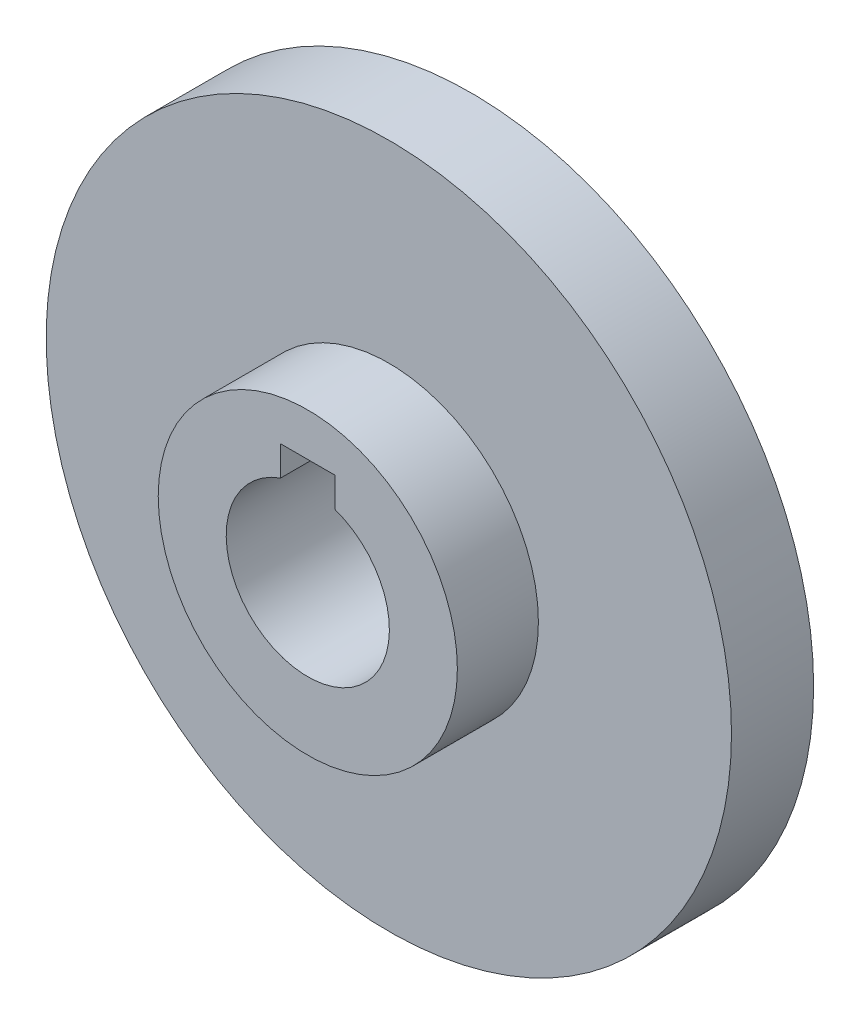
SolidWorks part; units mm, degrees
ref_plane "Front Plane" through (0, 0, 0) normal (0, 0, 1) x (1, 0, 0)
ref_plane "Top Plane" through (0, 0, 0) normal (0, 1, 0) x (1, 0, 0)
ref_plane "Right Plane" through (0, 0, 0) normal (1, 0, 0) x (0, 0, -1)
sketch "Sketch2" plane through (0, 0, 0) normal (0, 0, 1) x (1, 0, 0)
  circle A0 centre (0, 0) radius 31.5
  circle A1 centre (0, 0) radius 7.5
  dimension "D1" = 63
  dimension "D2" = 15
extrude "Boss-Extrude1" add sketch "Sketch2" along normal blind 7.55
sketch "Sketch4" plane through (0, 0, 7.55) normal (0, 0, 1) x (1, 0, 0)
  circle A0 centre (0, 0) radius 13.75
  circle A1 centre (0, 0) radius 7.5
  dimension "D1" = 27.5
extrude "Boss-Extrude2" add sketch "Sketch4" along normal blind 7.45
sketch "Sketch5" plane through (0, 0, 15) normal (0, 0, 1) x (1, 0, 0)
  line L0 (-2.5, 9.8) -> (-2.5, 7.0711)
  line L1 (-2.5, 7.0711) -> (2.5, 7.0711)
  line L2 (2.5, 7.0711) -> (2.5, 9.8)
  line L3 (2.5, 9.8) -> (-2.5, 9.8)
  circle A0 centre (0, 0) radius 7.5
  dimension "D3" = 15
  dimension "D1" = 5
  dimension "D2" = 9.8
extrude "Cut-Extrude1" cut sketch "Sketch5" against normal through all contours A0 L2 L3 L0
